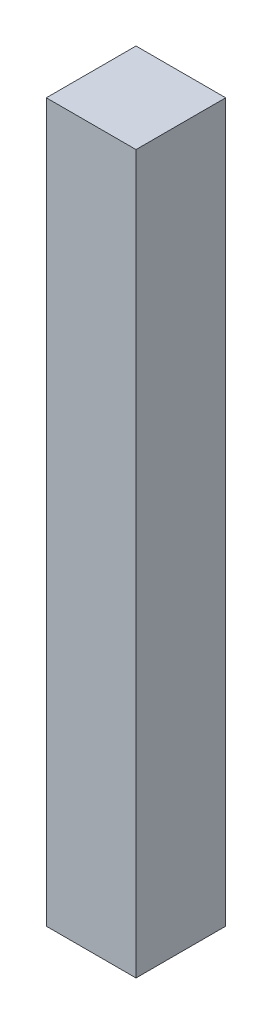
SolidWorks part; units mm, degrees
ref_plane "Front Plane" through (0, 0, 0) normal (0, 0, 1) x (1, 0, 0)
ref_plane "Top Plane" through (0, 0, 0) normal (0, 1, 0) x (1, 0, 0)
ref_plane "Right Plane" through (0, 0, 0) normal (1, 0, 0) x (0, 0, -1)
sketch "Sketch1" plane through (0, 0, 0) normal (0, 1, 0) x (1, 0, 0)
  line L1 (-25.4, -25.4) -> (25.4, -25.4)
  line L2 (-25.4, -25.4) -> (-25.4, 25.4)
  line L3 (-25.4, 25.4) -> (25.4, 25.4)
  line L4 (25.4, -25.4) -> (25.4, 25.4)
  line L5 (-25.4, -25.4) -> (25.4, 25.4) construction
  line L6 (-25.4, 25.4) -> (25.4, -25.4) construction
  point P0 (0, 0)
  dimension "D1" = 50.8
extrude "Boss-Extrude1" add sketch "Sketch1" along normal blind 406.4
